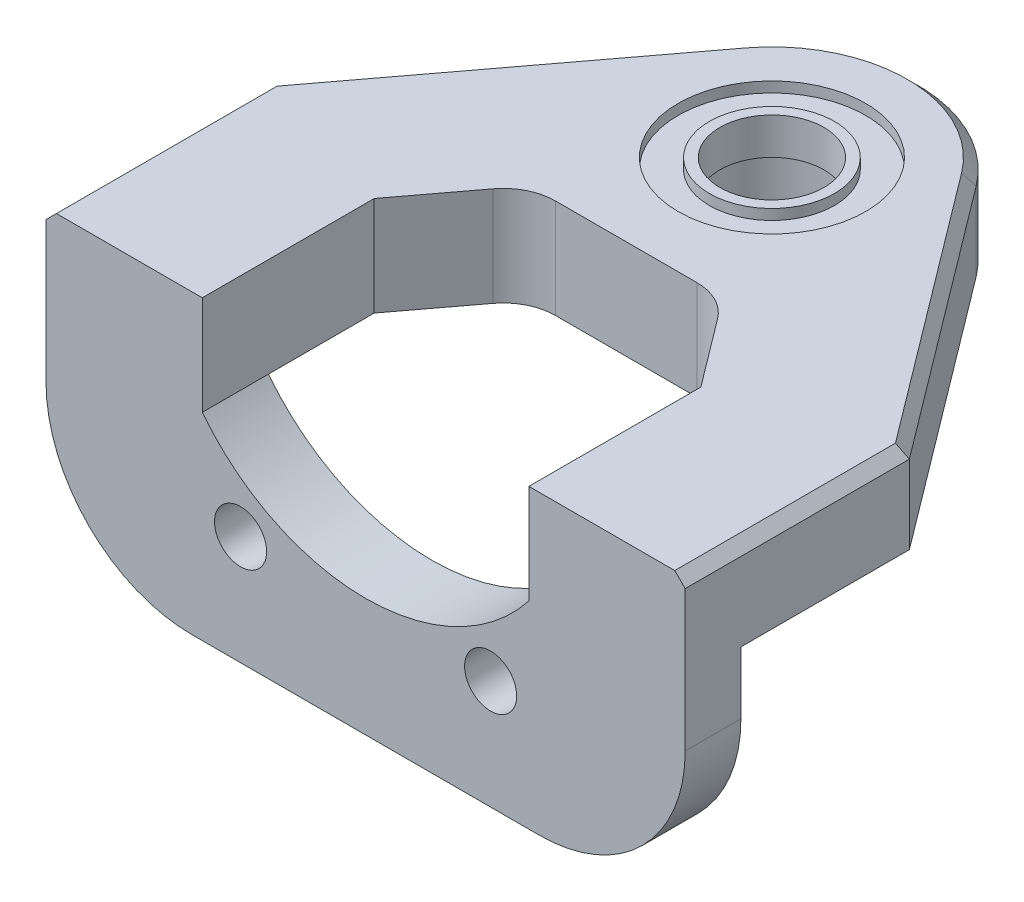
SolidWorks part; units mm, degrees
ref_plane "Front Plane" through (0, 0, 0) normal (0, 0, 1) x (1, 0, 0)
ref_plane "Top Plane" through (0, 0, 0) normal (0, 1, 0) x (1, 0, 0)
ref_plane "Right Plane" through (0, 0, 0) normal (1, 0, 0) x (0, 0, -1)
sketch "Sketch1" plane through (0, 0, 0) normal (0, 1, 0) x (1, 0, 0)
  line L0 (0, 0) -> (0, 32.65) construction
  line L5 (-30.675, 0) -> (-15.675, 0)
  line L8 (15.675, 0) -> (30.675, 0)
  line L13 (-30.675, 0) -> (-30.675, 15.1675)
  line L14 (-30.675, 15.1675) -> (-11.1869, 41.0675)
  line L17 (30.675, 15.1675) -> (11.1869, 41.0675)
  line L20 (30.675, 0) -> (30.675, 15.1675)
  line L21 (-9.2827, 18.65) -> (9.2827, 18.65)
  line L22 (-9.2827, 18.65) -> (-15.675, 10.1545)
  line L23 (-15.675, 10.1545) -> (-15.675, 0)
  line L24 (9.2827, 18.65) -> (15.675, 10.1545)
  line L25 (15.675, 10.1545) -> (15.675, 0)
  circle A3 centre (0, 32.65) radius 5
  arc A5 (11.1869, 41.0675) -> (-11.1869, 41.0675) centre (0, 32.65) ccw
  point P7 (-15.675, 7.7888)
  dimension "D2" = 30.675
  dimension "D3" = 15
  dimension "D4" = 10
  dimension "D5" = 14
  dimension "D7" = 14
  dimension "D1" = 32.65
  dimension "D6" = 15
extrude "Boss-Extrude1" add sketch "Sketch1" along normal mid plane 9.525
sketch "Sketch2" plane through (0, 4.7625, 0) normal (0, 1, 0) x (1, 0, 0)
  circle A0 centre (0, 32.65) radius 6
  circle A1 centre (0, 32.65) radius 9
  dimension "D1" = 18
  dimension "D2" = 12
extrude "Cut-Extrude1" cut sketch "Sketch2" against normal blind 1
fillet "Fillet1" radius 5 2 edges at (-9.2827, 0, -18.65) (9.2827, 0, -18.65)
sketch "Sketch3" plane through (0, -4.7625, 0) normal (0, -1, 0) x (1, 0, 0)
  circle A0 centre (0, -32.65) radius 6
  dimension "D1" = 12
extrude "Cut-Extrude2" cut sketch "Sketch3" against normal blind 6
mirror "Mirror2" about plane through (0, 0, 0) normal (0, 1, 0) of "Cut-Extrude1"
sketch "Sketch4" plane through (0, 0, 0) normal (0, 0, 1) x (1, 0, 0)
  line L0 (-16.675, -23.7375) -> (16.675, -23.7375)
  line L1 (-35.5012, -36.2835) -> (43.0291, -36.2835) construction
  line L2 (-30.675, -9.7375) -> (-30.675, 4.7625)
  line L3 (30.675, -9.7375) -> (30.675, 4.7625)
  line L4 (-30.675, 4.7625) -> (-15.675, 4.7625)
  line L5 (15.675, 4.7625) -> (30.675, 4.7625)
  line L6 (0, -23.7375) -> (0, 7.525) construction
  line L7 (-30.675, 4.7625) -> (-15.675, 4.7625) construction
  line L8 (-30.675, 4.7625) -> (-30.675, -4.7625) construction
  line L10 (-30.675, -4.7625) -> (-15.675, -4.7625) construction
  line L11 (15.675, 4.7625) -> (15.675, -4.7625)
  line L12 (-15.675, 4.7625) -> (-15.675, -4.7625)
  line L14 (81.1778, 38.7875) -> (-81.1778, 38.7875) construction
  line L15 (0, 7.525) -> (0, 31.525) construction
  line L16 (0, 7.525) -> (134.5926, 7.525) construction
  line L17 (81.1778, -23.7375) -> (-81.1778, -23.7375) construction
  line L18 (81.1778, -23.7375) -> (-81.1778, -23.7375) construction
  line L19 (0, 7.525) -> (-12, -13.2596) construction
  line L20 (0, 7.525) -> (12, -13.2596) construction
  line L22 (-15.675, 4.7625) -> (-15.675, -4.7625) construction
  line L23 (15.675, 4.7625) -> (15.675, -4.7625) construction
  line L25 (15.675, -4.7625) -> (30.675, -4.7625) construction
  arc A1 (-16.675, -23.7375) -> (-30.675, -9.7375) centre (-16.675, -9.7375) cw
  arc A2 (16.675, -23.7375) -> (30.675, -9.7375) centre (16.675, -9.7375) ccw
  arc A3 (-10, -9.7955) -> (10, -9.7955) centre (0, 7.525) ccw construction
  circle A4 centre (0, 7.525) radius 24 construction
  circle A12 centre (20.7846, -4.475) radius 2 construction
  circle A13 centre (0, -16.475) radius 2 construction
  circle A14 centre (-20.7846, -4.475) radius 2 construction
  circle A16 centre (-12, -13.2596) radius 2.5
  arc A17 (-15.675, -4.7625) -> (15.675, -4.7625) centre (0, 7.525) ccw
  circle A18 centre (12, -13.2596) radius 2.5
  point P4 (-4.8262, -36.2835)
  point P38 (166.9555, 39.9987)
  dimension "D5" = 14
  dimension "D6" = 48
  dimension "D7" = 40
  dimension "D11" = 5
  dimension "D12" = 5
  dimension "D2" = 31.2625
  dimension "D4" = 28.5
  dimension "D8" = 30
  dimension "D9" = 30
  dimension "D10" = 31.2625
extrude "Boss-Extrude2" add sketch "Sketch4" along normal blind 6.35
chamfer "Chamfer3" distance 1 angle 45 15 edges at (-20.9309, 4.7625, -28.1175) (0, 4.7625, -46.65) (20.9309, 4.7625, -28.1175) (30.675, 4.7625, -4.4088) (-30.675, 4.7625, -4.4088) (30.675, -4.7625, -7.5838) (30.675, -7.25, 0) (26.5745, -19.637, 0) (0, -23.7375, 0) (-26.5745, -19.637, 0) (-30.675, -4.7625, -7.5838) (-30.675, -7.25, 0) (20.9309, -4.7625, -28.1175) (-20.9309, -4.7625, -28.1175) (0, -4.7625, -46.65)
